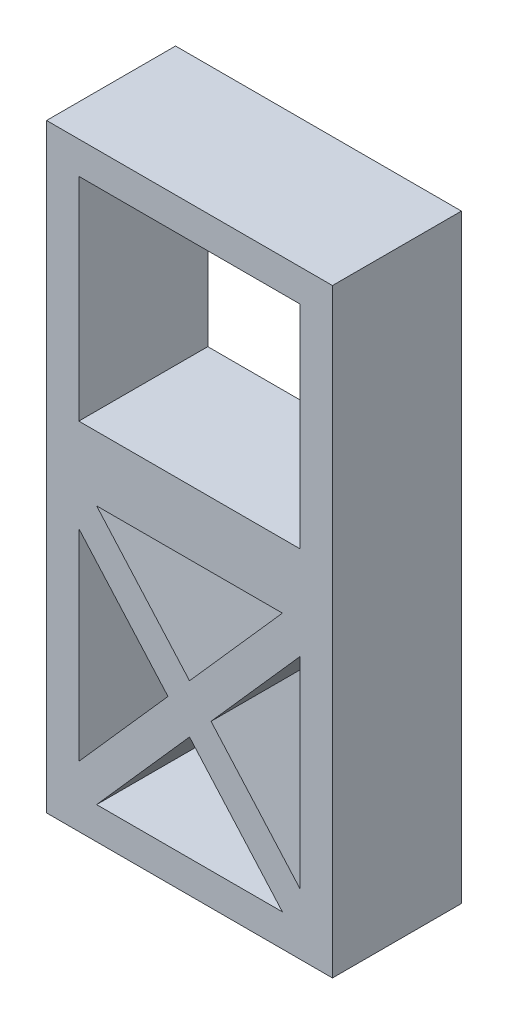
SolidWorks part; units mm, degrees
ref_plane "Front Plane" through (0, 0, 0) normal (0, 0, 1) x (1, 0, 0)
ref_plane "Top Plane" through (0, 0, 0) normal (0, 1, 0) x (1, 0, 0)
ref_plane "Right Plane" through (0, 0, 0) normal (1, 0, 0) x (0, 0, -1)
sketch "Sketch1" plane through (0, 0, 0) normal (0, 0, 1) x (1, 0, 0)
  line L0 (-28.15, -27.225) -> (28.15, -27.225) construction
  line L6 (-28.15, -27.225) -> (-28.15, 27.225)
  line L7 (-28.15, 27.225) -> (28.15, 27.225)
  line L8 (28.15, -27.225) -> (28.15, 27.225)
  line L9 (-28.15, 27.225) -> (28.15, -27.225) construction
  line L10 (-28.15, -27.225) -> (28.15, 27.225) construction
  line L11 (-21.8, 20.875) -> (21.8, 20.875)
  line L12 (-21.8, 20.875) -> (-21.8, -20.875)
  line L13 (-21.8, -20.875) -> (21.8, -20.875)
  line L14 (21.8, 20.875) -> (21.8, -20.875)
  line L15 (-21.8, 20.875) -> (21.8, -20.875) construction
  line L16 (-21.8, -20.875) -> (21.8, 20.875) construction
  line L17 (-28.15, -27.225) -> (-28.15, -90.875)
  line L18 (-28.15, -90.875) -> (28.15, -90.875)
  line L19 (28.15, -27.225) -> (28.15, -90.875)
  line L20 (-28.15, -27.225) -> (28.15, -90.875) construction
  line L21 (-28.15, -90.875) -> (28.15, -27.225) construction
  line L22 (-18.2945, -33.575) -> (0, -54.2578)
  line L23 (21.8, -39.1962) -> (4.2388, -59.05)
  line L24 (18.2945, -33.575) -> (0, -54.2578)
  line L26 (-4.2388, -59.05) -> (-21.8, -78.9038)
  line L27 (4.2388, -59.05) -> (21.8, -78.9038)
  line L28 (0, -63.8422) -> (-18.2945, -84.525)
  line L29 (0, -63.8422) -> (18.2945, -84.525)
  line L30 (-18.2945, -33.575) -> (18.2945, -33.575)
  line L31 (21.8, -39.1962) -> (21.8, -78.9038)
  line L32 (18.2945, -84.525) -> (-18.2945, -84.525)
  line L33 (-21.8, -78.9038) -> (-21.8, -39.1962)
  line L34 (-21.8, -39.1962) -> (-4.2388, -59.05)
  point P0 (0, 0)
  point P8 (0, 0)
  point P9 (0, 0)
  dimension "D8" = 6.35
  dimension "D1" = 6.35
  dimension "D2" = 41.75
  dimension "D3" = 6.35
  dimension "D4" = 43.6
  dimension "D5" = 70
  dimension "D6" = 3.175
  dimension "D7" = 3.175
  dimension "D10" = 6.35
  dimension "D12" = 3.175
  dimension "D13" = 3.175
  dimension "D14" = 3.175
extrude "Boss-Extrude1" add sketch "Sketch1" along normal blind 25.4
